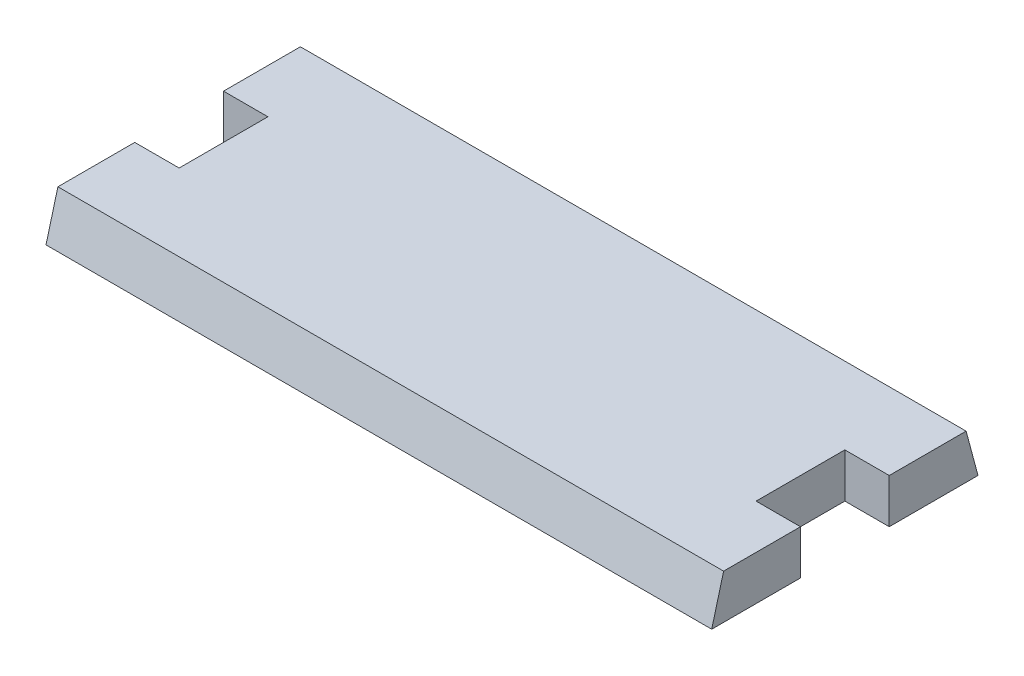
SolidWorks part; units mm, degrees
ref_plane "Front Plane" through (0, 0, 0) normal (0, 0, 1) x (1, 0, 0)
ref_plane "Top Plane" through (0, 0, 0) normal (0, 1, 0) x (1, 0, 0)
ref_plane "Right Plane" through (0, 0, 0) normal (1, 0, 0) x (0, 0, -1)
sketch "Sketch1" plane through (0, 0, 0) normal (0, 1, 0) x (1, 0, 0)
  line L0 (75, 10) -> (75, 30)
  line L1 (-75, -30) -> (75, -30)
  line L2 (-75, -30) -> (-75, -10)
  line L3 (-75, 30) -> (75, 30)
  line L4 (75, -30) -> (75, -10)
  line L5 (-75, -30) -> (75, 30) construction
  line L6 (-75, 30) -> (75, -30) construction
  line L7 (75, 10) -> (65, 10)
  line L8 (0, 0) -> (0, 49.676)
  line L9 (75, -10) -> (65, -10)
  line L10 (65, 10) -> (65, -10)
  line L11 (-75, -10) -> (-65, -10)
  line L12 (-75, 10) -> (-65, 10)
  line L13 (-65, 10) -> (-65, -10)
  line L14 (-75, 10) -> (-75, 30)
  point P0 (0, 0)
  dimension "D1" = 150
  dimension "D2" = 60
  dimension "D3" = 10
  dimension "D4" = 20
  dimension "D5" = 20
extrude "Boss-Extrude2" add sketch "Sketch1" along normal blind 10
draft "Draft2" type of draft neutral plane draft angle 15 faces to draft 2 face at (0, 5, -30) face at (0, 5, 30) neutral plane through (0, 0, 0) neutral plane normal (0, -1, 0) reverse direction yes parameters "D1"=15
